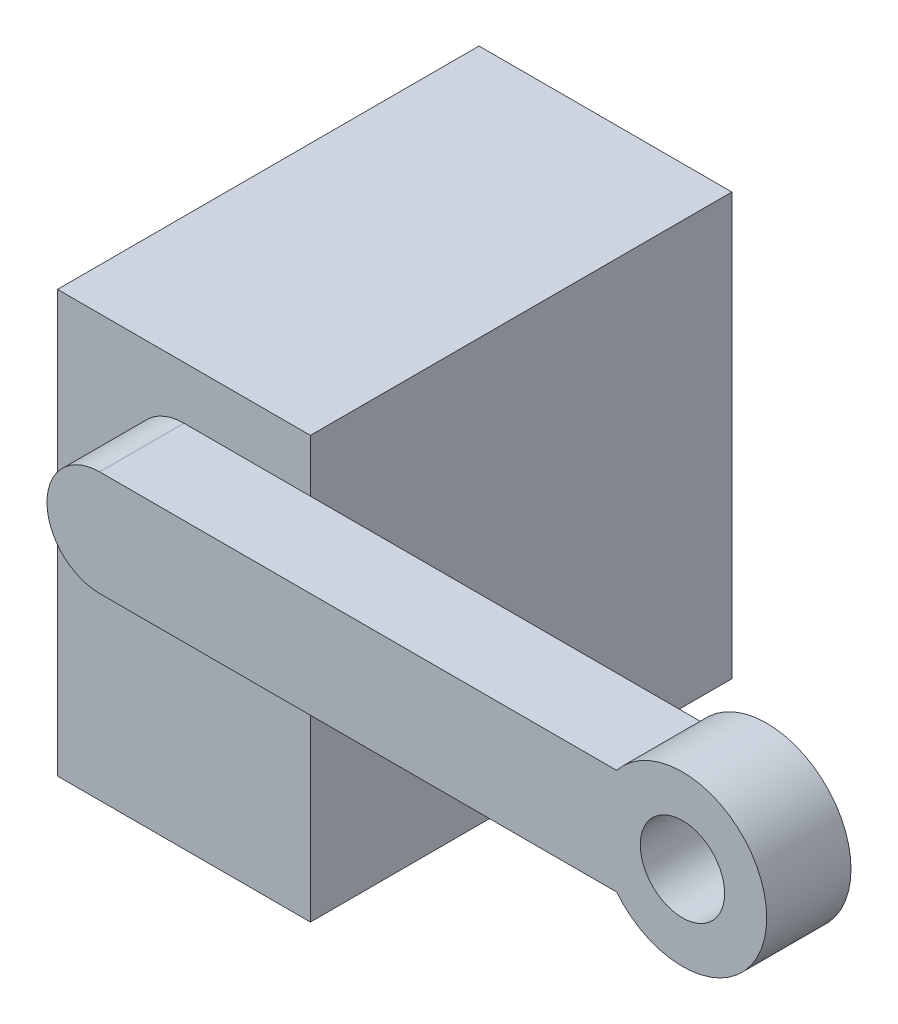
SolidWorks part; units mm, degrees
ref_plane "Plan de face" through (0, 0, 0) normal (0, 0, 1) x (1, 0, 0)
ref_plane "Plan de dessus" through (0, 0, 0) normal (0, 1, 0) x (1, 0, 0)
ref_plane "Plan de droite" through (0, 0, 0) normal (1, 0, 0) x (0, 0, -1)
sketch "Esquisse1" plane through (0, 0, 0) normal (0, 0, 1) x (1, 0, 0)
  line L1 (-6, -10) -> (6, -10)
  line L2 (-6, -10) -> (-6, 10)
  line L3 (-6, 10) -> (6, 10)
  line L4 (6, -10) -> (6, 10)
  line L5 (-6, -10) -> (6, 10) construction
  line L6 (-6, 10) -> (6, -10) construction
  point P0 (0, 0)
  dimension "D1" = 12
  dimension "D2" = 20
extrude "Boss.-Extru.1" add sketch "Esquisse1" along normal blind 20
sketch "Esquisse2" plane through (0, 0, 20) normal (0, 0, 1) x (1, 0, 0)
  line L0 (0, 0) -> (-6, 0) construction
  line L1 (-6, 10) -> (-6, -10) construction
  line L2 (-6, 0) -> (6, 10) construction
  line L3 (0, 7.5) -> (24.5287, 7.5)
  line L4 (0, 2.5) -> (24.5287, 2.5)
  arc A0 (0, 7.5) -> (0, 2.5) centre (0, 5) ccw
  arc A1 (24.5287, 2.5) -> (24.5287, 7.5) centre (27.6512, 5) ccw
  circle A2 centre (27.6512, 5) radius 2
  dimension "D1" = 5
  dimension "D2" = 2
  dimension "D3" = 4
extrude "Boss.-Extru.2" add sketch "Esquisse2" along normal blind 4
